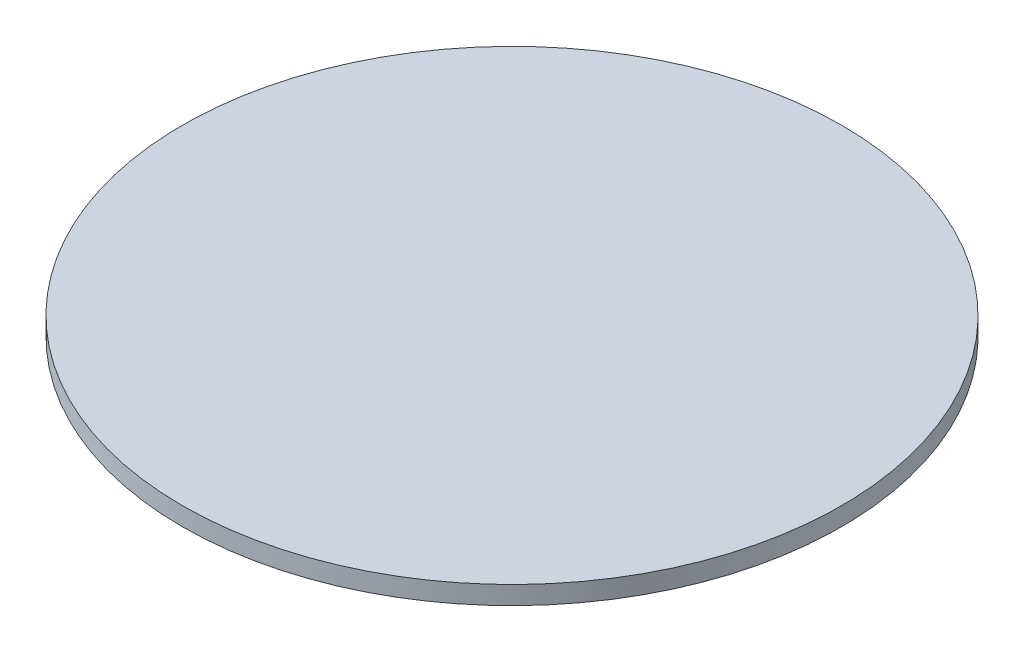
SolidWorks part; units mm, degrees
material "Oak"
ref_plane "Front Plane" through (0, 0, 0) normal (0, 0, 1) x (1, 0, 0)
ref_plane "Top Plane" through (0, 0, 0) normal (0, 1, 0) x (1, 0, 0)
ref_plane "Right Plane" through (0, 0, 0) normal (1, 0, 0) x (0, 0, -1)
sketch "Sketch1" plane through (0, 0, 0) normal (0, 1, 0) x (1, 0, 0)
  circle A0 centre (0, 0) radius 27
extrude "Boss-Extrude1" add sketch "Sketch1" along normal blind 1.5
